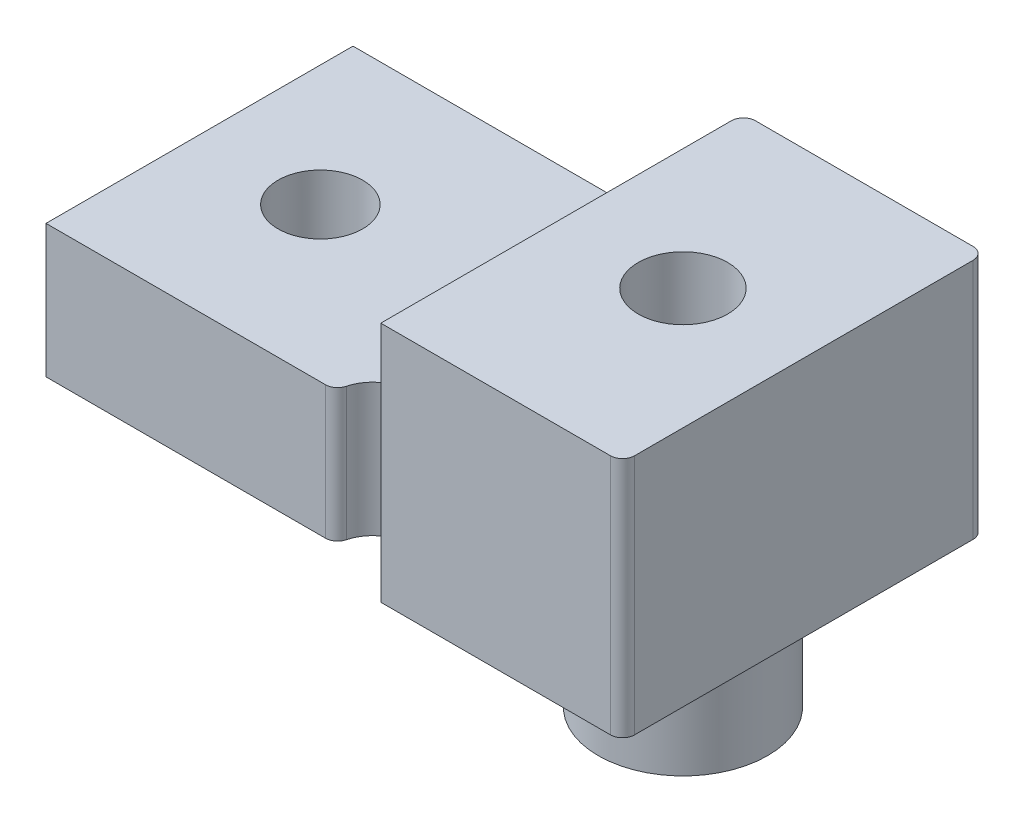
SolidWorks part; units mm, degrees
ref_plane "Front Plane" through (0, 0, 0) normal (0, 0, 1) x (1, 0, 0)
ref_plane "Top Plane" through (0, 0, 0) normal (0, 1, 0) x (1, 0, 0)
ref_plane "Right Plane" through (0, 0, 0) normal (1, 0, 0) x (0, 0, -1)
sketch "Sketch1" plane through (0, 0, 0) normal (0, 1, 0) x (1, 0, 0)
  line L1 (0, 0) -> (12, 0)
  line L2 (0, 0) -> (0, 12.7)
  line L3 (0, 12.7) -> (12, 12.7)
  line L4 (0, 6.35) -> (25, 6.35) construction
  line L5 (15, -1.15) -> (25, -1.15)
  line L6 (15, -1.15) -> (15, 0)
  line L7 (15, 13.85) -> (25, 13.85)
  line L8 (25, -1.15) -> (25, 13.85)
  line L9 (12, 0) -> (15, 0) construction
  line L10 (12, 12.7) -> (15, 12.7) construction
  line L11 (15, 13.85) -> (15, 12.7)
  arc A0 (15, 0) -> (12, 0) centre (13.5, 0) ccw
  circle A1 centre (5, 6.35) radius 1.75
  circle A2 centre (20, 6.35) radius 1.75
  arc A3 (15, 12.7) -> (12, 12.7) centre (13.5, 12.7) cw
  dimension "D4" = 15
  dimension "D8" = 3.5
  dimension "D1" = 12.7
  dimension "D2" = 10
  dimension "D3" = 3
  dimension "D5" = 15
  dimension "D6" = 5
  dimension "D9" = 5
extrude "Boss-Extrude1" add sketch "Sketch1" along normal blind 10
sketch "Sketch2" plane through (0, 10, 0) normal (0, 1, 0) x (1, 0, 0)
  line L1 (0, 0) -> (15, 0)
  line L2 (0, 0) -> (0, 12.7)
  line L3 (0, 12.7) -> (15, 12.7)
  line L4 (15, 0) -> (15, 12.7)
extrude "Cut-Extrude1" cut sketch "Sketch2" against normal blind 4.5
fillet "Fillet1" radius 0.5 5 edges at (25, 5, -13.85) (25, 5, 1.15) (12, 2.75, 0) (12, 2.75, -12.7) (15, 5, -13.85)
sketch "Sketch3" plane through (0, 0, 0) normal (0, -1, 0) x (1, 0, 0)
  circle A0 centre (20, -6.35) radius 3.5
  circle A1 centre (20, -6.35) radius 1.75 construction
  circle A2 centre (20, -6.35) radius 1.75
  dimension "D1" = 7
extrude "Boss-Extrude2" add sketch "Sketch3" along normal offset from surface (5 mm away) 15 up to face at (20.6577, 10, -7.3648)
sketch "Sketch4" plane through (0, -5, 0) normal (0, -1, 0) x (1, 0, 0)
  circle A0 centre (20, -6.35) radius 1.85
  dimension "D1" = 3.7
extrude "Cut-Extrude2" cut sketch "Sketch4" against normal through all
sketch "Sketch5" plane through (0, -5, 0) normal (0, -1, 0) x (1, 0, 0)
  circle A0 centre (20, -6.35) radius 1.95
  dimension "D1" = 3.9
extrude "Cut-Extrude3" cut sketch "Sketch5" against normal blind 4
